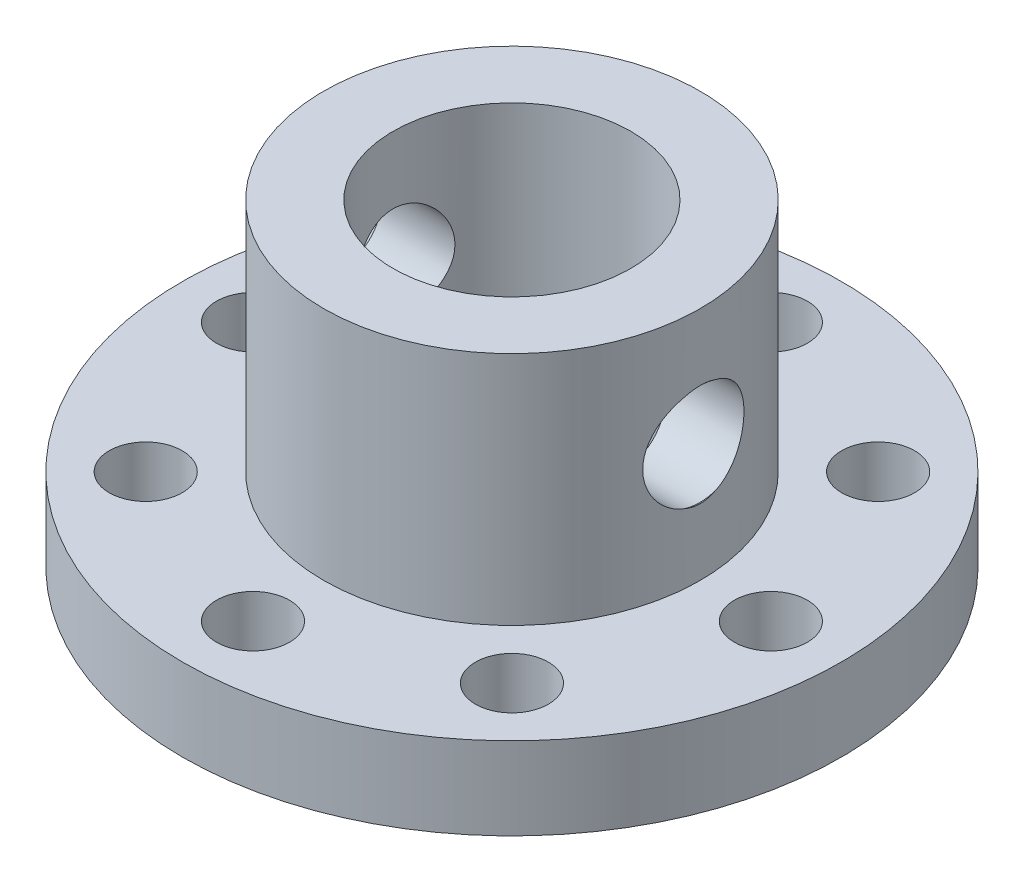
SolidWorks part; units mm, degrees
material "6061 Alloy"
ref_plane "Front Plane" through (0, 0, 0) normal (0, 0, 1) x (1, 0, 0)
ref_plane "Top Plane" through (0, 0, 0) normal (0, 1, 0) x (1, 0, 0)
ref_plane "Right Plane" through (0, 0, 0) normal (1, 0, 0) x (0, 0, -1)
sketch "Sketch1" plane through (0, 0, 0) normal (0, 1, 0) x (1, 0, 0)
  circle A0 centre (0, 0) radius 14
  dimension "D1" = 28
extrude "Boss-Extrude1" add sketch "Sketch1" along normal mid plane 3.5 contours A0
sketch "Sketch2" plane through (0, 1.75, 0) normal (0, 1, 0) x (1, 0, 0)
  line L0 (2.7822, 0.7455) -> (2.5435, 0.3349)
  line L1 (2.5435, 0.3349) -> (2.8804, 0)
  line L2 (2.8804, 0) -> (2.5435, -0.3349)
  line L3 (2.7822, -0.7455) -> (2.5435, -0.3349)
  line L4 (2.7822, -0.7455) -> (2.3701, -0.9817)
  line L5 (2.4945, -1.4402) -> (2.3701, -0.9817)
  line L6 (2.4945, -1.4402) -> (2.0353, -1.5617)
  line L7 (2.0367, -2.0367) -> (2.0353, -1.5617)
  line L8 (2.0367, -2.0367) -> (1.5617, -2.0353)
  line L9 (1.4402, -2.4945) -> (1.5617, -2.0353)
  line L10 (1.4402, -2.4945) -> (0.9817, -2.3701)
  line L11 (0.7455, -2.7822) -> (0.9817, -2.3701)
  line L12 (0.7455, -2.7822) -> (0.3349, -2.5435)
  line L13 (0, -2.8804) -> (0.3349, -2.5435)
  line L14 (0, -2.8804) -> (-0.3349, -2.5435)
  line L15 (-0.7455, -2.7822) -> (-0.3349, -2.5435)
  line L16 (-0.7455, -2.7822) -> (-0.9817, -2.3701)
  line L17 (-1.4402, -2.4945) -> (-0.9817, -2.3701)
  line L18 (-1.4402, -2.4945) -> (-1.5617, -2.0353)
  line L19 (-2.0367, -2.0367) -> (-1.5617, -2.0353)
  line L20 (-2.0367, -2.0367) -> (-2.0353, -1.5617)
  line L21 (-2.4945, -1.4402) -> (-2.0353, -1.5617)
  line L22 (-2.4945, -1.4402) -> (-2.3701, -0.9817)
  line L23 (-2.7822, -0.7455) -> (-2.3701, -0.9817)
  line L24 (-2.7822, -0.7455) -> (-2.5435, -0.3349)
  line L25 (-2.8804, 0) -> (-2.5435, -0.3349)
  line L26 (-2.8804, 0) -> (-2.5435, 0.3349)
  line L27 (-2.7822, 0.7455) -> (-2.5435, 0.3349)
  line L28 (-2.7822, 0.7455) -> (-2.3701, 0.9817)
  line L29 (-2.4945, 1.4402) -> (-2.3701, 0.9817)
  line L30 (-2.4945, 1.4402) -> (-2.0353, 1.5617)
  line L31 (-2.0367, 2.0367) -> (-2.0353, 1.5617)
  line L32 (-2.0367, 2.0367) -> (-1.5617, 2.0353)
  line L33 (-1.4402, 2.4945) -> (-1.5617, 2.0353)
  line L34 (-1.4402, 2.4945) -> (-0.9817, 2.3701)
  line L35 (-0.7455, 2.7822) -> (-0.9817, 2.3701)
  line L36 (-0.7455, 2.7822) -> (-0.3349, 2.5435)
  line L37 (0, 2.8804) -> (-0.3349, 2.5435)
  line L38 (0, 2.8804) -> (0.3349, 2.5435)
  line L39 (0.7455, 2.7822) -> (0.3349, 2.5435)
  line L40 (0.7455, 2.7822) -> (0.9817, 2.3701)
  line L41 (1.4402, 2.4945) -> (0.9817, 2.3701)
  line L42 (1.4402, 2.4945) -> (1.5617, 2.0353)
  line L43 (2.0367, 2.0367) -> (1.5617, 2.0353)
  line L44 (2.0367, 2.0367) -> (2.0353, 1.5617)
  line L45 (2.4945, 1.4402) -> (2.0353, 1.5617)
  line L46 (2.4945, 1.4402) -> (2.3701, 0.9817)
  line L47 (2.7822, 0.7455) -> (2.3701, 0.9817)
sketch "Sketch4" plane through (0, 1.75, 0) normal (0, 1, 0) x (1, 0, 0)
  circle A0 centre (0, 0) radius 5
  circle A1 centre (-7.7782, 7.7782) radius 1.025
  circle A2 centre (-7.7782, -7.7782) radius 1.025
  circle A3 centre (7.7782, -7.7782) radius 1.025
  circle A4 centre (7.7782, 7.7782) radius 1.025
  circle A5 centre (11, 0) radius 1.025
  circle A6 centre (0, -11) radius 1.025
  circle A7 centre (-11, 0) radius 1.025
  circle A8 centre (0, 11) radius 1.025
  circle A9 centre (0, 0) radius 14
hole_wizard "M2.5 Clearance Hole1" positions "Sketch5" profile "Sketch6" hole size "M2.5" standard "ANSI Metric"
sketch "Sketch5" plane through (0, 1.75, 0) normal (0, 1, 0) x (1, 0, 0)
  point P0 (-11, 0)
  point P3 (-7.7782, 7.7782)
  point P6 (0, 11)
  point P9 (7.7782, 7.7782)
  point P12 (11, 0)
  point P15 (7.7782, -7.7782)
  point P18 (0, -11)
  point P21 (-7.7782, -7.7782)
sketch "Sketch6" plane through (-11, 1.75, 0) normal (1, 0, 0) x (0, 0, 1)
  line L0 (0, 0) -> (0, 6.9313)
  line L1 (0, 6.9313) -> (1.55, 6)
  line L2 (1.55, 6) -> (1.55, 0)
  line L5 (1.55, 0) -> (0, 0)
  line L10 (0, 6.9313) -> (-1.55, 6) construction
  line L11 (0, -6.35) -> (0, 107.95) construction
  dimension "Hole Dia." = 3.1
  dimension "Hole Depth" = 6
  dimension "Drill Angle" = 118
sketch "Sketch7" plane through (0, -1.75, 0) normal (0, -1, 0) x (1, 0, 0)
  circle A0 centre (0, 0) radius 5.05
  dimension "D1" = 10.1
sketch "Sketch9" plane through (0, 1.75, 0) normal (0, 1, 0) x (1, 0, 0)
  circle A0 centre (0, 0) radius 8
  dimension "D1" = 16
extrude "Boss-Extrude2" add sketch "Sketch9" along normal blind 10
sketch "Sketch15" plane through (0, 11.75, 0) normal (0, 1, 0) x (1, 0, 0)
  circle A0 centre (0, 0) radius 5
  dimension "D1" = 10
extrude "Cut-Extrude-Thin1" [suppressed] cut sketch "Sketch15" against normal offset from surface (29 mm away) 4 thin
sketch "Sketch11" plane through (0, 11.75, 0) normal (0, 1, 0) x (1, 0, 0)
  circle A0 centre (0, 0) radius 16
  dimension "D1" = 32
extrude "Boss-Extrude3" [suppressed] add sketch "Sketch11" against normal blind 6
sketch "Sketch12" [suppressed] plane through (0, 34.75, 0) normal (0, 1, 0) x (1, 0, 0)
  line L1 (8, 8) -> (-8, 8) construction
  line L2 (8, 8) -> (8, -8) construction
  line L3 (8, -8) -> (-8, -8) construction
  line L4 (-8, 8) -> (-8, -8) construction
  line L5 (8, 8) -> (-8, -8) construction
  line L6 (8, -8) -> (-8, 8) construction
  point P0 (0, 0)
  dimension "D1" = 16
  dimension "D2" = 16
hole_wizard "Tap Drill for M4x0.7 Tap1" [suppressed] positions "Sketch13" profile "Sketch14" hole size "M4x0.7" standard "ANSI Metric"
sketch "Sketch13" [suppressed] plane through (0, 34.75, 0) normal (0, 1, 0) x (1, 0, 0)
  point P0 (-8, 8)
  point P3 (-8, -8)
  point P6 (8, -8)
  point P9 (8, 8)
sketch "Sketch14" plane through (-8, 34.75, -8) normal (1, 0, 0) x (0, 0, 1)
  line L0 (0, 0) -> (0, 36.5)
  line L1 (0, 36.5) -> (1.65, 36.5)
  line L2 (1.65, 36.5) -> (1.65, 0)
  line L5 (1.65, 0) -> (0, 0)
  line L11 (0, -6.35) -> (0, 107.95) construction
  dimension "Thru Hole Dia." = 3.3
  dimension "Thru Hole Depth" = 36.5
extrude "Cut-Extrude1" cut sketch "Sketch7" against normal through all contours A0
sketch "Sketch16" plane through (0, 0, 0) normal (1, 0, 0) x (0, 0, -1)
  line L0 (8, 11.75) -> (-8, 11.75) construction
  circle A0 centre (0, 6.75) radius 2
  dimension "D1" = 4
  dimension "D3" = 0
  dimension "D2" = 5
ref_plane "Plane1" through (8, 0, 0) normal (1, 0, 0) x (0, 0, -1)
sketch "Sketch22" plane through (8, 0, 0) normal (1, 0, 0) x (0, 0, -1)
  circle A0 centre (0, 6.75) radius 2
  dimension "D1" = 4
hole_wizard "M4 Clearance Hole1" positions "Sketch24" profile "Sketch25" hole size "M4" standard "ANSI Metric"
sketch "Sketch24" plane through (8, 0, 0) normal (1, 0, 0) x (0, 0, -1)
  point P0 (0, 6.75)
sketch "Sketch25" plane through (8, 6.75, 0) normal (0, 1, 0) x (0, 0, -1)
  line L0 (0, 0) -> (0, 26.6919)
  line L1 (0, 26.6919) -> (2.15, 25.4)
  line L2 (2.15, 25.4) -> (2.15, 0.025)
  line L3 (2.15, 0.025) -> (2.175, 0)
  line L5 (2.175, 0) -> (0, 0)
  line L6 (-2.15, 0.025) -> (-2.175, 0) construction
  line L10 (0, 26.6919) -> (-2.15, 25.4) construction
  line L11 (0, -6.35) -> (0, 107.95) construction
  dimension "Hole Dia." = 4.3
  dimension "Hole Depth" = 25.4
  dimension "Near C'Sink Dia." = 4.35
  dimension "Near C'Sink Angle" = 90
  dimension "Drill Angle" = 118
